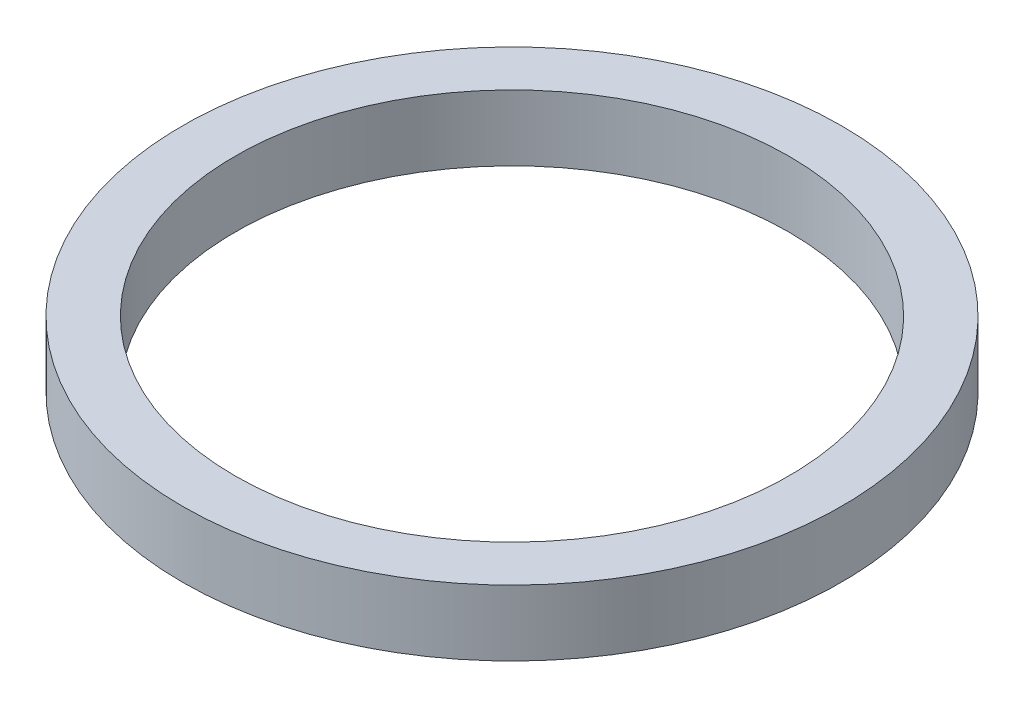
SolidWorks part; units mm, degrees
ref_plane "Alzado" through (0, 0, 0) normal (0, 0, 1) x (1, 0, 0)
ref_plane "Planta" through (0, 0, 0) normal (0, 1, 0) x (1, 0, 0)
ref_plane "Vista lateral" through (0, 0, 0) normal (1, 0, 0) x (0, 0, -1)
sketch "Croquis1" plane through (0, 0, 0) normal (0, 1, 0) x (1, 0, 0)
  circle A0 centre (0, 0) radius 21.05
  circle A1 centre (0, 0) radius 25.05
  dimension "D1" = 42.1
  dimension "D2" = 4
extrude "Saliente-Extruir1" add sketch "Croquis1" along normal blind 5
